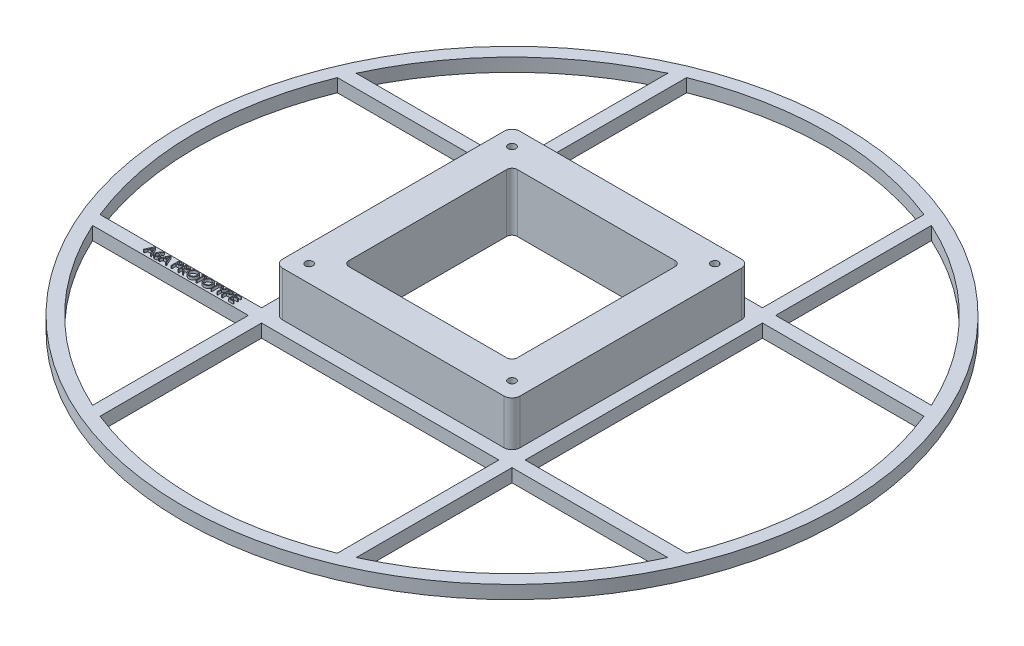
SolidWorks part; units mm, degrees
ref_plane "Front Plane" through (0, 0, 0) normal (0, 0, 1) x (1, 0, 0)
ref_plane "Top Plane" through (0, 0, 0) normal (0, 1, 0) x (1, 0, 0)
ref_plane "Right Plane" through (0, 0, 0) normal (1, 0, 0) x (0, 0, -1)
sketch "Sketch1" plane through (0, 0, 0) normal (0, 1, 0) x (1, 0, 0)
  line L0 (-125, 0) -> (125, 0) construction
  line L1 (0, -125) -> (0, 125) construction
  line L11 (-50, -50) -> (50, -50)
  line L12 (-50, -50) -> (-50, 50)
  line L13 (-50, 50) -> (50, 50)
  line L14 (50, -50) -> (50, 50)
  line L15 (-50, -50) -> (50, 50) construction
  line L16 (-50, 50) -> (50, -50) construction
  circle A0 centre (0, 0) radius 125
  circle A1 centre (0, 0) radius 120
  dimension "D1" = 250
  dimension "D3" = 100
  dimension "D2" = 5
extrude "Boss-Extrude1" add sketch "Sketch1" along normal blind 5 contours A0 A1 | L11 L14 L13 L12
sketch "Sketch2" plane through (-50, 0, 0) normal (-1, 0, 0) x (0, 0, 1)
  line L0 (50, 0) -> (-50, 0) construction
  line L1 (-50, 5) -> (-45, 5)
  line L2 (-50, 5) -> (-50, 0)
  line L3 (-50, 0) -> (-45, 0)
  line L4 (-45, 5) -> (-45, 0)
  dimension "D1" = 5
extrude "Boss-Extrude2" add sketch "Sketch2" along normal up to next
mirror "Mirror1" about plane through (0, 0, 0) normal (1, 0, 0) of "Boss-Extrude2" second plane through (0, 0, 0) second plane normal (0, 0, 1)
sketch "Sketch5" plane through (0, 5, 0) normal (0, 1, 0) x (1, 0, 0)
  line L0 (-50, 45) -> (-50, 50) construction
  line L1 (-109.0871, 50) -> (109.0871, 50) construction
  line L2 (-50, 50) -> (50, -50) construction
  line L3 (-109.0871, -50) -> (109.0871, -50) construction
  line L4 (50, 45) -> (50, 50) construction
  line L5 (50, 50) -> (-50, -50) construction
ref_plane "Plane1" through (0, 0, 0) normal (-0.7071, 0, 0.7071) x (0.7071, 0, 0.7071)
ref_plane "Plane2" through (0, 0, 0) normal (-0.7071, 0, -0.7071) x (-0.7071, 0, 0.7071)
mirror "Mirror2" about plane through (0, 0, 0) normal (-0.7071, 0, -0.7071) of "Boss-Extrude2" second plane through (0, 0, 0) second plane normal (-0.7071, 0, 0.7071)
mirror "Mirror3" about plane through (0, 0, 0) normal (1, 0, 0) of "Mirror2"
sketch "Sketch8" plane through (0, 5, 0) normal (0, 1, 0) x (1, 0, 0)
  line L0 (-50, 50) -> (50, -50) construction
  line L1 (-45, 45) -> (45, 45)
  line L2 (-45, 45) -> (-45, -45)
  line L3 (-45, -45) -> (45, -45)
  line L4 (45, 45) -> (45, -45)
extrude "Boss-Extrude3" add sketch "Sketch8" along normal blind 17
fillet "Fillet1" radius 3 4 edges at (-45, 13.5, -45) (45, 13.5, -45) (45, 13.5, 45) (-45, 13.5, 45)
sketch "Sketch9" plane through (0, 22, 0) normal (0, 1, 0) x (1, 0, 0)
  line L0 (-50, 50) -> (50, -50) construction
  circle A0 centre (-38.4645, 38.4645) radius 1.45
  arc A1 (-42, 45) -> (-45, 42) centre (-42, 42) ccw construction
  circle A2 centre (38.4645, 38.4645) radius 1.45
  circle A3 centre (38.4645, -38.4645) radius 1.45
  circle A4 centre (-38.4645, -38.4645) radius 1.45
  point P16 (0, 0)
  dimension "D1" = 2.9
  dimension "D2" = 5
  dimension "D3" = 4
extrude "Cut-Extrude1" cut sketch "Sketch9" against normal blind 15
sketch "Sketch11" plane through (0, 5, 0) normal (0, 1, 0) x (1, 0, 0)
  text T0 "A6A PROTOTYPE"
extrude "Boss-Extrude4" add sketch "Sketch11" along normal blind 1
sketch "Sketch13" plane through (0, 22, 0) normal (0, 1, 0) x (1, 0, 0)
  line L0 (-31.9289, 31.9289) -> (-45, 45) construction
  line L1 (-50, 50) -> (50, -50) construction
  line L2 (137.5, 137.5) -> (-137.5, -137.5) construction
  line L4 (-31.9289, 31.9289) -> (31.9289, 31.9289)
  line L5 (-31.9289, 31.9289) -> (-31.9289, -31.9289)
  line L6 (-31.9289, -31.9289) -> (31.9289, -31.9289)
  line L7 (31.9289, 31.9289) -> (31.9289, -31.9289)
  point P6 (-38.4645, 38.4645)
  point P9 (31.9289, -31.9289)
extrude "Cut-Extrude2" cut sketch "Sketch13" against normal up to next
fillet "Fillet2" radius 2 4 edges at (31.9289, 11, 31.9289) (-31.9289, 11, 31.9289) (31.9289, 11, -31.9289) (-31.9289, 11, -31.9289)
